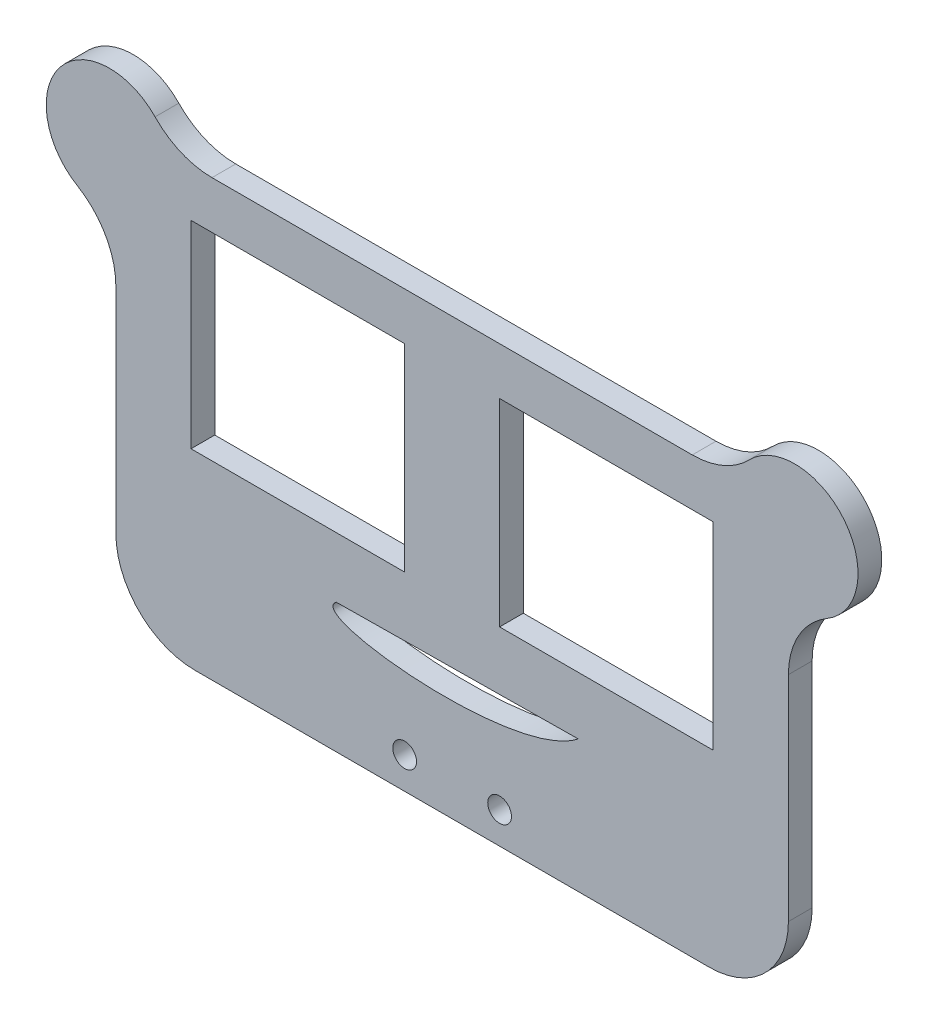
SolidWorks part; units mm, degrees
ref_plane "Front Plane" through (0, 0, 0) normal (0, 0, 1) x (1, 0, 0)
ref_plane "Top Plane" through (0, 0, 0) normal (0, 1, 0) x (1, 0, 0)
ref_plane "Right Plane" through (0, 0, 0) normal (1, 0, 0) x (0, 0, -1)
sketch "Sketch1" plane through (0, 0, 0) normal (0, 0, 1) x (1, 0, 0)
  line L1 (-42.5, 27.5) -> (42.5, 27.5)
  line L2 (-42.5, 27.5) -> (-42.5, -27.5)
  line L3 (-42.5, -27.5) -> (42.5, -27.5)
  line L4 (42.5, 27.5) -> (42.5, -27.5)
  line L5 (-42.5, 27.5) -> (42.5, -27.5) construction
  line L6 (-42.5, -27.5) -> (42.5, 27.5) construction
  point P0 (0, 0)
  dimension "D1" = 85
  dimension "D2" = 55
extrude "Boss-Extrude2" add sketch "Sketch1" along normal blind 3 contours L2 L3 L4 L1
sketch "Sketch3" plane through (0, 0, 3) normal (0, 0, 1) x (1, 0, 0)
  line L0 (0, 27.5) -> (0, -27.5) construction
  line L1 (-33, 21.5) -> (-6, 21.5)
  line L2 (-33, 21.5) -> (-33, -3.5)
  line L3 (-33, -3.5) -> (-6, -3.5)
  line L4 (-6, 21.5) -> (-6, -3.5)
  line L5 (-42.5, 27.5) -> (42.5, 27.5) construction
  line L6 (-42.5, -27.5) -> (42.5, -27.5) construction
  line L7 (33, -3.5) -> (6, -3.5)
  line L8 (6, 21.5) -> (6, -3.5)
  line L9 (33, 21.5) -> (6, 21.5)
  line L10 (33, 21.5) -> (33, -3.5)
  dimension "D1" = 27
  dimension "D2" = 25
  dimension "D3" = 6
  dimension "D4" = 6
extrude "Cut-Extrude1" cut sketch "Sketch3" against normal through all both and the other way through all
fillet "Fillet2" radius 10 2 edges at (-42.5, -27.5, 1.5) (42.5, -27.5, 1.5)
sketch "Sketch4" plane through (0, 0, 0) normal (0, 0, 1) x (1, 0, 0)
  line L0 (0, 27.5) -> (0, -27.5) construction
  line L1 (-42.5, 27.5) -> (42.5, 27.5) construction
  line L2 (-32.5, -27.5) -> (32.5, -27.5) construction
  line L3 (-43.3013, 25) -> (54.2008, -31.2928) construction
  circle A0 centre (-43.3013, 25) radius 8
  circle A2 centre (43.3013, 25) radius 8
  point P2 (0, 0)
  dimension "D3" = 16
  dimension "D1" = 60
  dimension "D2" = 50
extrude "Boss-Extrude3" add sketch "Sketch4" along normal blind 3
fillet "Fillet3" radius 10 4 edges at (42.5, 17.0402, 1.5) (35.7019, 27.5, 1.5) (-35.7019, 27.5, 1.5) (-42.5, 17.0402, 1.5)
sketch "Sketch5" plane through (0, 0, 3) normal (0, 0, 1) x (1, 0, 0)
  line L0 (0, 27.5) -> (0, -27.5) construction
  line L1 (-30.3494, 27.5) -> (30.3494, 27.5) construction
  line L2 (-32.5, -27.5) -> (32.5, -27.5) construction
  line L3 (-14.6572, -11.1186) -> (15.9375, -10.7884)
  spline S0 degree 3 poles (-14.6572, -11.1186) (-18.5338, -14.1875) (7.468, -17.1497) (15.8017, -10.8975) (15.9375, -10.7884) knots 0 0 0 0 0.491907 0.500883 0.500883 0.500883 0.500883
extrude "Cut-Extrude2" cut sketch "Sketch5" against normal through all both and the other way through all
sketch "Sketch6" plane through (0, 0, 3) normal (0, 0, 1) x (1, 0, 0)
  line L0 (0, 27.5) -> (0, -27.5) construction
  line L1 (-30.3494, 27.5) -> (30.3494, 27.5) construction
  line L2 (-32.5, -27.5) -> (32.5, -27.5) construction
  line L3 (-6, -23.5) -> (6, -23.5) construction
  circle A0 centre (-6, -23.5) radius 1.5
  circle A1 centre (6, -23.5) radius 1.5
  point P9 (0, -23.5)
  dimension "D3" = 3
  dimension "D4" = 3
  dimension "D1" = 12
  dimension "D2" = 4
extrude "Cut-Extrude3" cut sketch "Sketch6" against normal through all both and the other way through all
